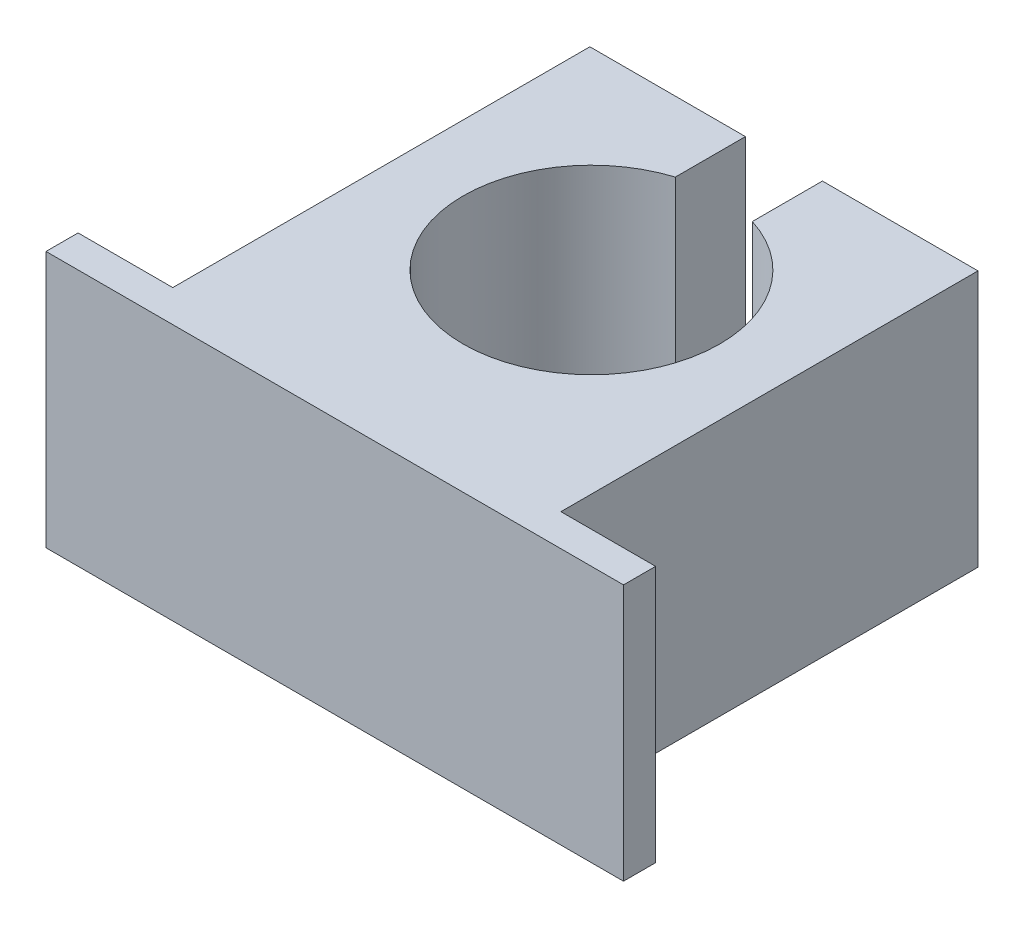
SolidWorks part; units mm, degrees
ref_plane "Front Plane" through (0, 0, 0) normal (0, 0, 1) x (1, 0, 0)
ref_plane "Top Plane" through (0, 0, 0) normal (0, 1, 0) x (1, 0, 0)
ref_plane "Right Plane" through (0, 0, 0) normal (1, 0, 0) x (0, 0, -1)
sketch "Sketch1" plane through (0, 0, 0) normal (0, 1, 0) x (1, 0, 0)
  line L1 (-45, 35) -> (45, 35)
  line L2 (-45, 35) -> (-45, -35)
  line L3 (-45, -35) -> (45, -35)
  line L4 (45, 35) -> (45, -35)
  line L5 (-45, 35) -> (45, -35) construction
  line L6 (-45, -35) -> (45, 35) construction
  point P0 (0, 0)
  dimension "D1" = 90
  dimension "D2" = 70
extrude "Boss-Extrude1" add sketch "Sketch1" along normal blind 40
sketch "Sketch4" plane through (0, 40, 0) normal (0, 1, 0) x (1, 0, 0)
  line L0 (0, 0) -> (0, 5) construction
  circle A0 centre (0, 5) radius 20
  dimension "D2" = 40
  dimension "D1" = 5
extrude "Cut-Extrude1" cut sketch "Sketch4" against normal blind 40
sketch "Sketch5" plane through (0, 40, 0) normal (0, 1, 0) x (1, 0, 0)
  line L0 (-45, 35) -> (-45, -35) construction
  line L1 (-45, 35) -> (-30.2446, 35)
  line L2 (-45, 35) -> (-45, -30)
  line L3 (-45, -30) -> (-30.2446, -30)
  line L4 (-30.2446, 35) -> (-30.2446, -30)
  line L5 (-45, -35) -> (45, -35) construction
  line L6 (0, 0) -> (0, 35) construction
  line L7 (45, -30) -> (30.2446, -30)
  line L8 (30.2446, 35) -> (30.2446, -30)
  line L9 (45, 35) -> (30.2446, 35)
  line L10 (45, 35) -> (45, -30)
  dimension "D2" = 5
extrude "Cut-Extrude2" cut sketch "Sketch5" against normal blind 40
sketch "Sketch6" plane through (0, 40, 0) normal (0, 1, 0) x (1, 0, 0)
  line L0 (30.2446, 35) -> (-30.2446, 35) construction
  line L1 (-6, 48.5116) -> (6, 48.5116)
  line L2 (-6, 48.5116) -> (-6, 21.4884)
  line L3 (-6, 21.4884) -> (6, 21.4884)
  line L4 (6, 48.5116) -> (6, 21.4884)
  line L5 (-6, 48.5116) -> (6, 21.4884) construction
  line L6 (-6, 21.4884) -> (6, 48.5116) construction
  point P0 (0, 35)
  dimension "D1" = 12
extrude "Cut-Extrude3" cut sketch "Sketch6" against normal blind 40
